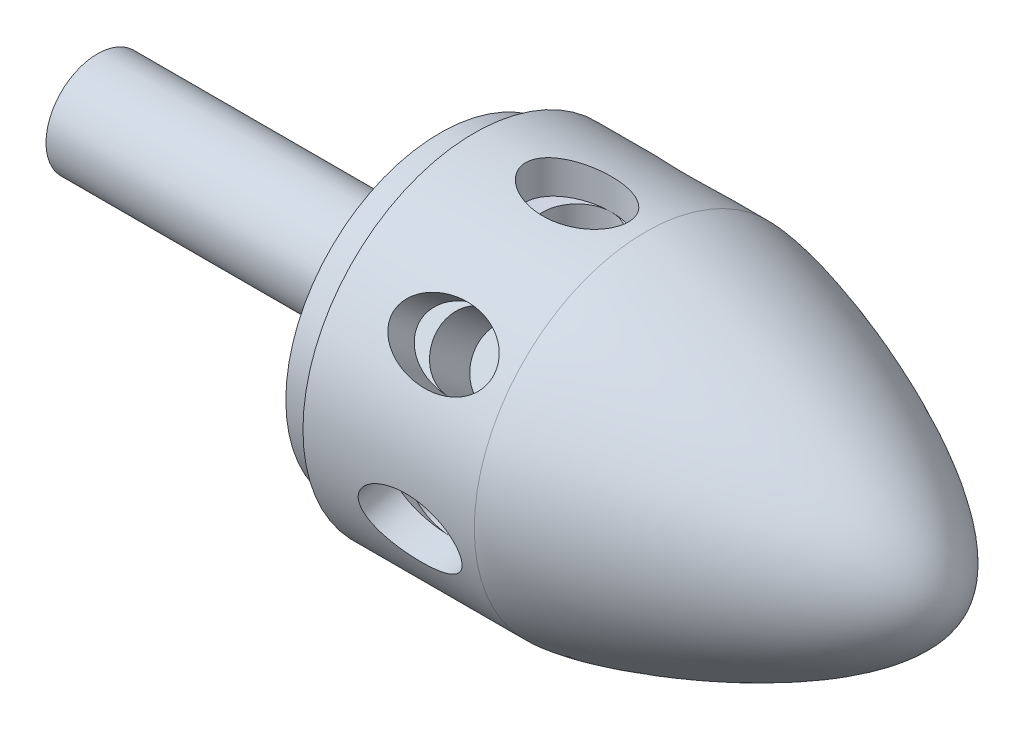
SolidWorks part; units mm, degrees
material "AISI 316 Annealed Stainless Steel Bar (SS)"
ref_plane "Front Plane" through (0, 0, 0) normal (0, 0, 1) x (1, 0, 0)
ref_plane "Top Plane" through (0, 0, 0) normal (0, 1, 0) x (1, 0, 0)
ref_plane "Right Plane" through (0, 0, 0) normal (1, 0, 0) x (0, 0, -1)
sketch "Sketch1" plane through (0, 0, 0) normal (0, 0, 1) x (1, 0, 0)
  line L0 (0, 0) -> (150, 0)
  line L2 (0, 45) -> (10, 45)
  line L3 (10, 45) -> (10, 50)
  line L4 (10, 50) -> (60, 50)
  line L5 (150, -70.7107) -> (150, 70.7107) construction
  line L6 (203.031, 50) -> (-83.031, 50) construction
  line L7 (0, 45) -> (0, 15)
  line L8 (0, 15) -> (-100, 15)
  line L9 (-100, 15) -> (-100, 0)
  line L10 (-100, 0) -> (0, 0)
  spline S0 degree 3 poles (60, 50) (76.6667, 50) (150, 25) (150, 0) knots 0 0 0 0 1 1 1 1
  dimension "D6" = 75
  dimension "D8" = 180
  dimension "D9" = 50
  dimension "D1" = 150
  dimension "D2" = 30
  dimension "D3" = 10
  dimension "D4" = 50
  dimension "D5" = 50
  dimension "D7" = 90
  dimension "D10" = 15
  dimension "D11" = 100
revolve "Revolve1" add sketch "Sketch1" angle 360 about L0
ref_plane "Plane2" through (0, 50, 0) normal (0, 1, 0) x (1, 0, 0)
sketch "Sketch2" plane through (0, 50, 0) normal (0, 1, 0) x (1, 0, 0)
  line L0 (60, 0) -> (10, 0) construction
  line L1 (138.5261, 0) -> (37.9478, 0) construction
  line L5 (10, 50) -> (10, -50) construction
  ellipse E0 centre (40, 0) end of major axis (25, 0) minor radius 10
  point P1 (0, 0)
  dimension "D1" = 15
  dimension "D2" = 10
  dimension "D3" = 30
extrude "Cut-Extrude1" cut sketch "Sketch2" against normal blind 10 contours E0
sketch "Sketch3" plane through (0, 40, 0) normal (0, 1, 0) x (1, 0, 0)
  line L0 (60, 0) -> (10, 0) construction
  line L1 (10, 50) -> (10, -50) construction
  circle A0 centre (40, 0) radius 10
  point P6 (0, 0)
  dimension "D1" = 20
  dimension "D2" = 30
extrude "Cut-Extrude2" cut sketch "Sketch3" against normal blind 15
pattern_circular "CirPattern1" count 7 over 360 about axis through (0, 0, 0) along (-1, 0, 0) of "Cut-Extrude1", "Cut-Extrude2"
